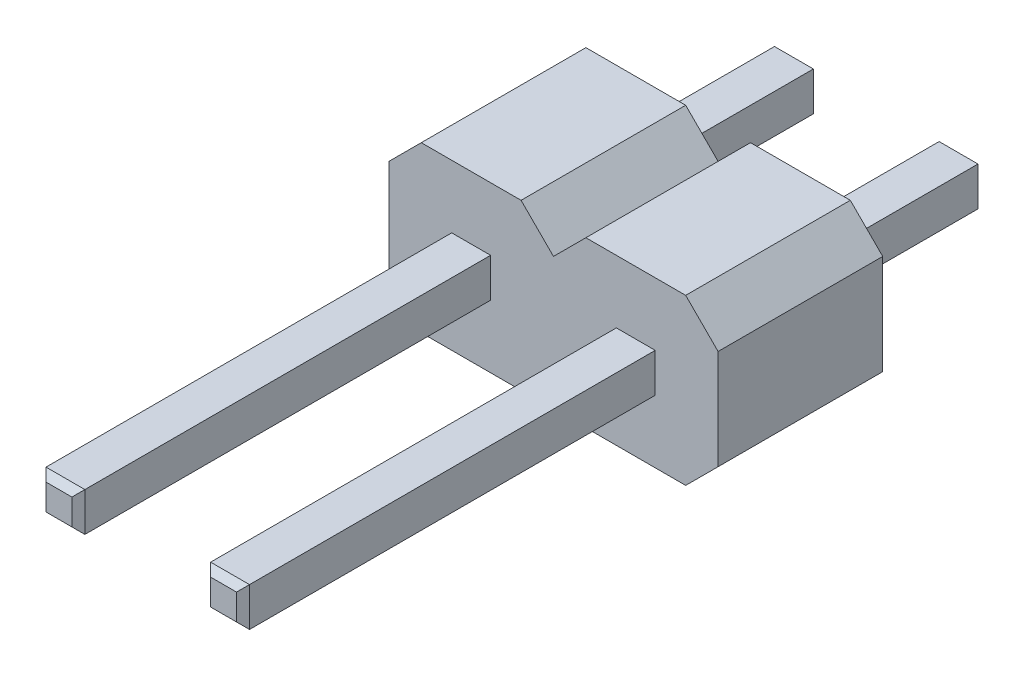
SolidWorks part; units mm, degrees
ref_plane "Front Plane" through (0, 0, 0) normal (0, 0, 1) x (1, 0, 0)
ref_plane "Top Plane" through (0, 0, 0) normal (0, 1, 0) x (1, 0, 0)
ref_plane "Right Plane" through (0, 0, 0) normal (1, 0, 0) x (0, 0, -1)
sketch "Sketch1" plane through (0, 0, 0) normal (0, 0, 1) x (1, 0, 0)
  line L0 (1.27, 0) -> (0, 0) construction
  line L5 (0, 0) -> (0, 1.27) construction
  line L6 (-0.77, 1.27) -> (0.77, 1.27)
  line L7 (0.77, 1.27) -> (1.27, 0.77)
  line L8 (1.27, 0.77) -> (1.27, -0.77)
  line L9 (-1.27, 0.77) -> (-1.27, -0.77)
  line L10 (-0.77, 1.27) -> (-1.27, 0.77)
  line L11 (0.77, -1.27) -> (1.27, -0.77)
  line L12 (-0.77, -1.27) -> (0.77, -1.27)
  line L13 (-0.77, -1.27) -> (-1.27, -0.77)
  point P4 (0, 0)
  point P13 (-1.27, 0)
  point P14 (0, 0)
  point P15 (0, 0)
  point P16 (-1.3282, 0.0309)
  point P17 (0, 0)
  dimension "D1" = 1.27
  dimension "D2" = 45
  dimension "D3" = 0.5
extrude "Plastic" add sketch "Sketch1" along normal blind 2.54
sketch "Sketch2" plane through (0, 0, 0) normal (1, 0, 0) x (0, 0, -1)
  line L0 (-8.9, 0.3) -> (-8.9, -0.3)
  line L1 (-8.9, 0) -> (2.54, 0) construction
  line L4 (-8.9, -0.3) -> (2.54, -0.3)
  line L6 (-8.9, 0.3) -> (2.54, 0.3)
  line L8 (2.54, -0.3) -> (2.54, 0.3)
  line L11 (-9.5, 4.63) -> (-9.5, 0.6) construction
  line L12 (-9.8, 4.63) -> (-9.8, 0.6) construction
  line L13 (-9.2, 4.63) -> (-9.2, 0.6) construction
  arc A3 (-9.8, 0.6) -> (-8.9, -0.3) centre (-8.9, 0.6) ccw construction
  arc A4 (-9.5, 0.6) -> (-8.9, 0) centre (-8.9, 0.6) ccw construction
  arc A5 (-9.2, 0.6) -> (-8.9, 0.3) centre (-8.9, 0.6) ccw construction
  point P6 (0, 0)
  point P22 (0.5758, 0.2967)
  point P30 (0.5805, 0.1553)
  dimension "D1" = 8.9
  dimension "D4" = 2.54
  dimension "D2" = 0.3
  dimension "D3" = 0.3
extrude "Contact" add sketch "Sketch2" along normal mid plane 0.6
chamfer "Chamfer1" distance 0.1 angle 45 8 edges at (0.3, 0, -2.54) (0, -0.3, -2.54) (-0.3, 0, -2.54) (0, 0.3, -2.54) (-0.3, 0, 8.9) (0, 0.3, 8.9) (0.3, 0, 8.9) (0, -0.3, 8.9)
pattern_linear "Линейный массив1" count 2 spacing 2.54 along (1, 0, 0) of "Contact", "Plastic", "Chamfer1"
